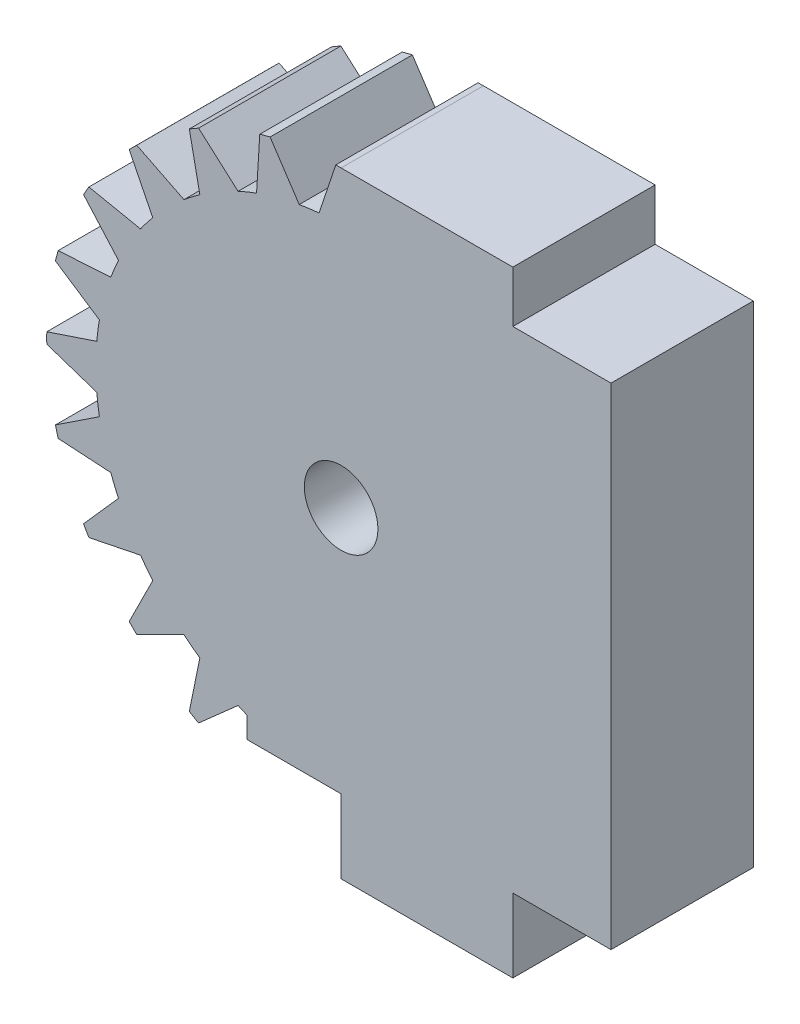
SolidWorks part; units mm, degrees
ref_plane "Front Plane" through (0, 0, 0) normal (0, 0, 1) x (1, 0, 0)
ref_plane "Top Plane" through (0, 0, 0) normal (0, 1, 0) x (1, 0, 0)
ref_plane "Right Plane" through (0, 0, 0) normal (1, 0, 0) x (0, 0, -1)
sketch "Sketch1" plane through (0, 0, 0) normal (0, 0, 1) x (1, 0, 0)
  circle A0 centre (0, 0) radius 10
  dimension "D1" = 20
extrude "Boss-Extrude1" add sketch "Sketch1" along normal blind 5.8
sketch "Sketch2" plane through (0, 0, 0) normal (0, 0, 1) x (1, 0, 0)
  line L2 (0, 12.65) -> (-0.9, 9.9594)
  line L3 (0, 12.65) -> (0.9, 9.9594)
  arc A0 (0.9, 9.9594) -> (-0.9, 9.9594) centre (0, 0) ccw
  dimension "D1" = 20
  dimension "D3" = 2.8371
  dimension "D4" = 1.8
extrude "Boss-Extrude2" add sketch "Sketch2" along normal blind 5.8
pattern_circular "CirPattern1" count 24 every 15 about axis through (0, 0, 0) along (0, 0, 1) of "Boss-Extrude2"
sketch "Sketch3" plane through (0, 0, 0) normal (0, 0, 1) x (1, 0, 0)
  circle A0 centre (0, 0) radius 12
  circle A1 centre (0, 0) radius 12.65
  dimension "D1" = 24
  dimension "D2" = 25.3
extrude "Cut-Extrude1" cut sketch "Sketch3" along normal blind 6
sketch "Sketch4" plane through (0, 0, 0) normal (0, 0, 1) x (1, 0, 0)
  line L0 (0, 0) -> (0, 12)
  line L2 (0, 0) -> (-3.8268, -9.2388)
  line L4 (-3.8268, -9.2388) -> (-4.5922, -11.0866)
  arc A0 (-4.5922, -11.0866) -> (0, 12) centre (0, 0) ccw
  arc A1 (0.2181, 11.998) -> (-0.2181, 11.998) centre (0, 0) ccw construction
  arc A2 (-4.2003, -9.0751) -> (-3.447, -9.3871) centre (0, 0) ccw construction
extrude "Cut-Extrude2" cut sketch "Sketch4" along normal blind 6
sketch "Sketch5" plane through (0, 0, 0) normal (0, 0, 1) x (1, 0, 0)
  circle A0 centre (0, 0) radius 1.5
  dimension "D1" = 3
extrude "Cut-Extrude3" cut sketch "Sketch5" along normal blind 6
sketch "Sketch6" plane through (0, 0, 0) normal (0, 0, 1) x (1, 0, 0)
  line L0 (0, 1.5) -> (0, 12)
  line L3 (11, 9.9045) -> (7, 9.9045)
  line L5 (7, 9.9045) -> (7, 12)
  line L6 (11, -10.0955) -> (11, 9.9045)
  line L7 (11, -10.0955) -> (7, -10.0955)
  line L8 (7, -10.0955) -> (7, -13.0955)
  line L10 (0, 12) -> (7, 12)
  line L14 (7, -13.0955) -> (0, -13.0955)
  line L15 (-3.8268, -10.0955) -> (0, -10.0955)
  line L16 (0, -10.0955) -> (0, -13.0955)
  line L17 (-0.574, -1.3858) -> (-3.8268, -9.2388)
  line L18 (-3.8268, -9.2388) -> (-3.8268, -10.0955)
  arc A0 (-0.574, -1.3858) -> (0, 1.5) centre (0, 0) ccw
  dimension "D2" = 2.0955
  dimension "D6" = 7
  dimension "D4" = 20
  dimension "D5" = 4
  dimension "D7" = 3
  dimension "D8" = 7
  dimension "D11" = 4
extrude "Boss-Extrude3" add sketch "Sketch6" along normal blind 5.8
sketch "Sketch7" [suppressed] plane through (0, 0, 6) normal (0, 0, 1) x (1, 0, 0)
  line L0 (-0.2181, 11.998) -> (7, 12)
  line L1 (7, 12) -> (7, 9.9045)
  line L2 (7, 9.9045) -> (11, 9.9045)
  line L3 (11, 9.9045) -> (11, -10.0955)
  line L4 (11, -10.0955) -> (7, -10.0955)
  line L5 (7, -10.0955) -> (7, -13.0955)
  line L6 (7, -13.0955) -> (0, -13.0955)
  line L7 (0, -13.0955) -> (0, -10.0955)
  line L8 (0, -10.0955) -> (-3.8268, -10.0955)
  line L9 (-3.8268, -10.0955) -> (-3.8268, -9.2388)
  line L10 (-0.2181, 11.998) -> (-0.9, 9.9594)
  line L11 (-1.7084, 9.853) -> (-2.8947, 11.6456)
  line L12 (-2.8947, 11.6456) -> (-3.316, 11.5328)
  line L13 (-3.316, 11.5328) -> (-3.447, 9.3871)
  line L14 (-4.2003, 9.0751) -> (-5.8101, 10.4996)
  line L15 (-5.8101, 10.4996) -> (-6.1879, 10.2815)
  line L16 (-6.1879, 10.2815) -> (-5.7591, 8.1751)
  line L17 (-6.406, 7.6788) -> (-8.3297, 8.6381)
  line L18 (-8.3297, 8.6381) -> (-8.6381, 8.3297)
  line L19 (-8.6381, 8.3297) -> (-7.6788, 6.406)
  line L20 (-8.1751, 5.7591) -> (-10.2815, 6.1879)
  line L21 (-10.2815, 6.1879) -> (-10.4996, 5.8101)
  line L22 (-10.4996, 5.8101) -> (-9.0751, 4.2003)
  line L23 (-9.3871, 3.447) -> (-11.5328, 3.316)
  line L24 (-11.5328, 3.316) -> (-11.6456, 2.8947)
  line L25 (-11.6456, 2.8947) -> (-9.853, 1.7084)
  line L26 (-9.9594, 0.9) -> (-11.998, 0.2181)
  line L27 (-11.998, 0.2181) -> (-11.998, -0.2181)
  line L28 (-11.998, -0.2181) -> (-9.9594, -0.9)
  line L29 (-9.853, -1.7084) -> (-11.6456, -2.8947)
  line L30 (-11.6456, -2.8947) -> (-11.5328, -3.316)
  line L31 (-11.5328, -3.316) -> (-9.3871, -3.447)
  line L32 (-9.0751, -4.2003) -> (-10.4996, -5.8101)
  line L33 (-10.4996, -5.8101) -> (-10.2815, -6.1879)
  line L34 (-10.2815, -6.1879) -> (-8.1751, -5.7591)
  line L35 (-7.6788, -6.406) -> (-8.6381, -8.3297)
  line L36 (-7.6788, -6.406) -> (-8.6381, -8.3297) construction
  line L37 (-8.6381, -8.3297) -> (-8.3297, -8.6381)
  line L38 (-8.3297, -8.6381) -> (-6.406, -7.6788)
  line L39 (-5.7591, -8.1751) -> (-6.1879, -10.2815)
  line L40 (-6.1879, -10.2815) -> (-5.8101, -10.4996)
  line L41 (-5.8101, -10.4996) -> (-4.2003, -9.0751)
  circle A0 centre (0, 0) radius 1.5
  arc A1 (-0.9, 9.9594) -> (-1.7084, 9.853) centre (0, 0) ccw
  arc A2 (-3.447, 9.3871) -> (-4.2003, 9.0751) centre (0, 0) ccw
  arc A3 (-5.7591, 8.1751) -> (-6.406, 7.6788) centre (0, 0) ccw
  arc A4 (-7.6788, 6.406) -> (-8.1751, 5.7591) centre (0, 0) ccw
  arc A5 (-9.0751, 4.2003) -> (-9.3871, 3.447) centre (0, 0) ccw
  arc A6 (-9.853, 1.7084) -> (-9.9594, 0.9) centre (0, 0) ccw
  arc A7 (-4.2003, -9.0751) -> (-3.8268, -9.2388) centre (0, 0) ccw
  arc A8 (-6.406, -7.6788) -> (-5.7591, -8.1751) centre (0, 0) ccw
  arc A9 (-8.1751, -5.7591) -> (-7.6788, -6.406) centre (0, 0) ccw
  arc A10 (-9.3871, -3.447) -> (-9.0751, -4.2003) centre (0, 0) ccw
  arc A11 (-9.9594, -0.9) -> (-9.853, -1.7084) centre (0, 0) ccw
